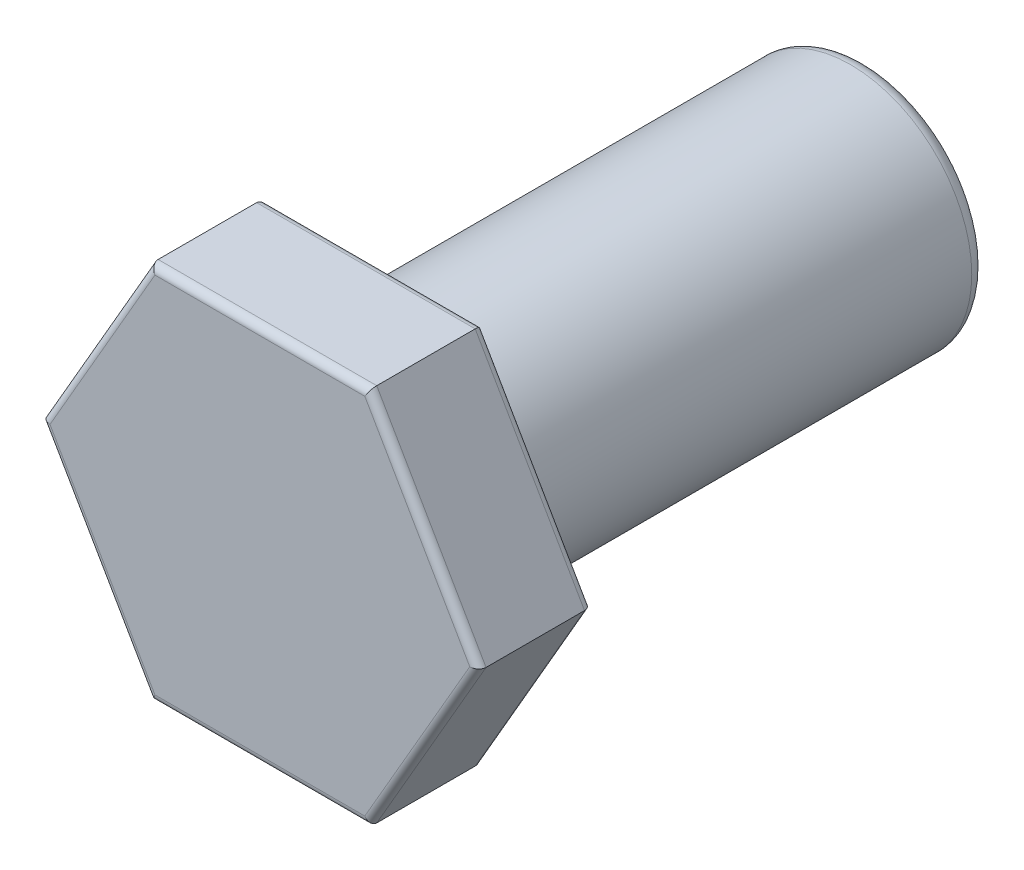
SolidWorks part; units mm, degrees
ref_plane "前视" through (0, 0, 0) normal (0, 0, 1) x (1, 0, 0)
ref_plane "上视" through (0, 0, 0) normal (0, 1, 0) x (1, 0, 0)
ref_plane "右视" through (0, 0, 0) normal (1, 0, 0) x (0, 0, -1)
sketch "草图1" plane through (0, 0, 0) normal (0, 0, 1) x (1, 0, 0)
  circle A0 centre (0, 0) radius 8
  dimension "D1" = 16
extrude "凸台-拉伸1" add sketch "草图1" along normal blind 32.5
sketch "草图2" plane through (0, 0, 32.5) normal (0, 0, 1) x (1, 0, 0)
  line L1 (7.2169, -12.5) -> (14.4338, 0)
  line L2 (14.4338, 0) -> (7.2169, 12.5)
  line L3 (7.2169, 12.5) -> (-7.2169, 12.5)
  line L4 (-7.2169, 12.5) -> (-14.4338, 0)
  line L5 (-14.4338, 0) -> (-7.2169, -12.5)
  line L6 (-7.2169, -12.5) -> (7.2169, -12.5)
  circle A0 centre (0, 0) radius 12.5 construction
  dimension "D1" = 25
extrude "凸台-拉伸2" add sketch "草图2" along normal blind 7.5
fillet "圆角1" radius 1 1 edges at (8, 0, 0)
fillet "圆角2" radius 0.5 12 edges at (0, -12.5, 32.5) (-10.8253, -6.25, 32.5) (-10.8253, 6.25, 32.5) (10.8253, -6.25, 40) (10.8253, -6.25, 32.5) (0, 12.5, 40) (0, 12.5, 32.5) (10.8253, 6.25, 32.5) (10.8253, 6.25, 40) (-10.8253, 6.25, 40) (-10.8253, -6.25, 40) (0, -12.5, 40)
